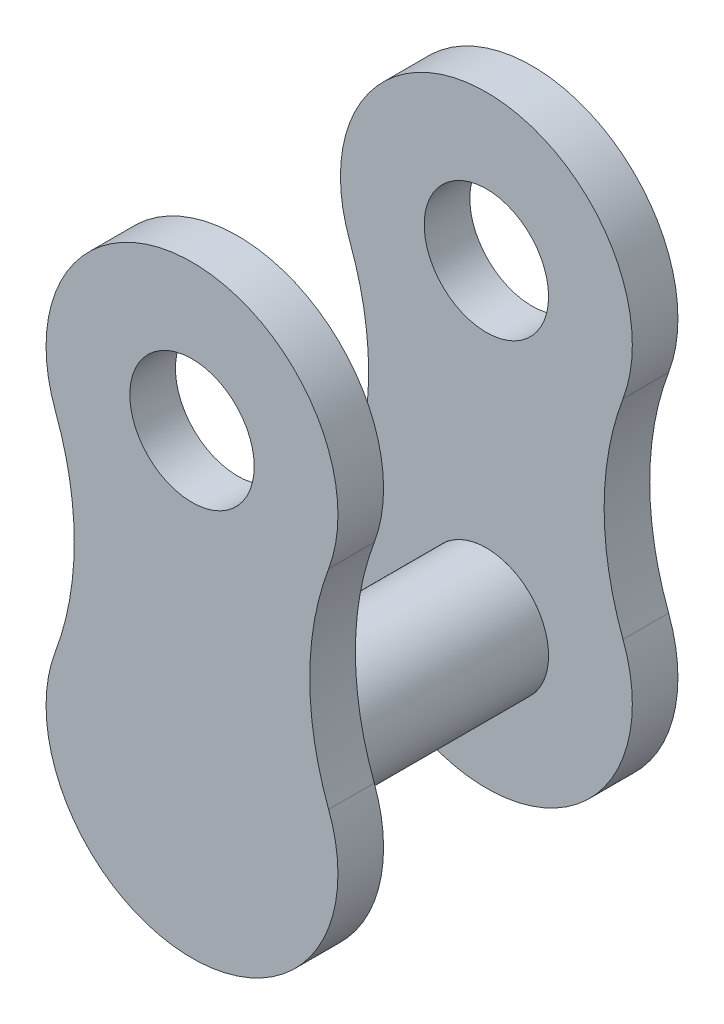
SolidWorks part; units mm, degrees
material "6061-T6 (SS)"
ref_plane "Front Plane" through (0, 0, 0) normal (0, 0, 1) x (1, 0, 0)
ref_plane "Top Plane" through (0, 0, 0) normal (0, 1, 0) x (1, 0, 0)
ref_plane "Right Plane" through (0, 0, 0) normal (1, 0, 0) x (0, 0, -1)
sketch "Sketch2" plane through (0, 0, 0) normal (0, 0, 1) x (1, 0, 0)
  line L0 (0, 0) -> (0, 9.525) construction
  line L1 (12.7, 4.7625) -> (-12.7, 4.7625) construction
  circle A0 centre (0, 0) radius 4.4704
  circle A1 centre (0, 9.525) radius 4.4704
  arc A2 (-4.1858, 1.5697) -> (-4.1858, 7.9553) centre (-12.7, 4.7625) ccw
  arc A3 (4.1858, 1.5697) -> (4.1858, 7.9553) centre (12.7, 4.7625) cw
  circle A4 centre (0, 9.525) radius 1.905
  circle A5 centre (0, 0) radius 1.905
  point P8 (0, 4.7625)
  dimension "D2" = 8.9408
  dimension "D4" = 3.81
  dimension "D1" = 9.525
  dimension "D3" = 25.4
extrude "Boss-Extrude1" add sketch "Sketch2" along normal blind 1.397 contours A0 A5 | A0 A3 A1 A2 | A1 A4
sketch "Sketch3" plane through (0, 0, 1.397) normal (0, 0, 1) x (1, 0, 0)
  circle A1 centre (0, 0) radius 1.905
extrude "Boss-Extrude2" add sketch "Sketch3" along normal blind 7.62
ref_plane "Plane1" through (0, 0, 5.207) normal (0, 0, 1) x (1, 0, 0)
sketch "Sketch5" plane through (0, 0, 9.017) normal (0, 0, 1) x (1, 0, 0)
  circle A0 centre (0, 9.525) radius 1.905
  arc A4 (-4.1858, 1.5697) -> (4.1858, 1.5697) centre (0, 0) ccw
  arc A5 (4.1858, 7.9553) -> (4.1858, 1.5697) centre (12.7, 4.7625) ccw
  arc A6 (4.1858, 7.9553) -> (-4.1858, 7.9553) centre (0, 9.525) ccw
  arc A7 (-4.1858, 1.5697) -> (-4.1858, 7.9553) centre (-12.7, 4.7625) ccw
  arc A8 (-4.1858, 1.5697) -> (4.1858, 1.5697) centre (0, 0) ccw
  arc A9 (4.1858, 7.9553) -> (4.1858, 1.5697) centre (12.7, 4.7625) ccw
  arc A10 (4.1858, 7.9553) -> (-4.1858, 7.9553) centre (0, 9.525) ccw
  arc A11 (-4.1858, 1.5697) -> (-4.1858, 7.9553) centre (-12.7, 4.7625) ccw
  dimension "D1" = 0
extrude "Boss-Extrude4" add sketch "Sketch5" along normal blind 1.397
ref_plane "Plane2" through (0, 0, 0) normal (0, 0, -1) x (-1, 0, 0)
sketch "Sketch6" plane through (0, 0, 10.414) normal (0, 0, 1) x (1, 0, 0)
  circle A0 centre (0, 0) radius 1.905
  circle A1 centre (0, 9.525) radius 1.905 construction
